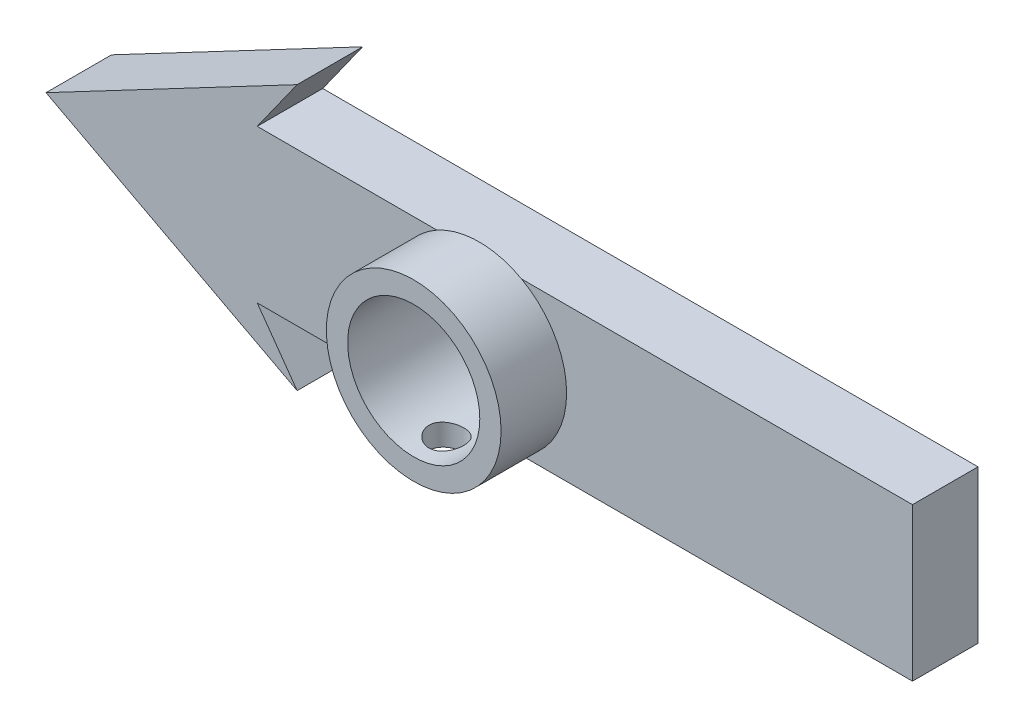
SolidWorks part; units mm, degrees
ref_plane "Front Plane" through (0, 0, 0) normal (0, 0, 1) x (1, 0, 0)
ref_plane "Top Plane" through (0, 0, 0) normal (0, 1, 0) x (1, 0, 0)
ref_plane "Right Plane" through (0, 0, 0) normal (1, 0, 0) x (0, 0, -1)
sketch "Sketch3" plane through (0, 0, 0) normal (0, 0, 1) x (1, 0, 0)
  line L0 (0, 0) -> (11.4976, 6.0667)
  line L1 (11.4976, 6.0667) -> (9.6701, 3.5)
  line L2 (9.6701, 3.5) -> (39.6701, 3.5)
  line L3 (39.6701, 3.5) -> (39.6701, -3.5)
  line L4 (3.3, 0) -> (-3.3, 0) construction
  line L5 (11.4976, -6.0667) -> (9.6701, -3.5)
  line L6 (9.6701, -3.5) -> (39.6701, -3.5)
  line L7 (0, 0) -> (11.4976, -6.0667)
  point P11 (39.6701, 0)
  dimension "D1" = 30
  dimension "D2" = 13
  dimension "D4" = 7
extrude "Boss-Extrude1" add sketch "Sketch3" along normal blind 3
sketch "Sketch8" plane through (0, 0, 3) normal (0, 0, 1) x (1, 0, 0)
  line L0 (0, 0) -> (39.6701, 0) construction
  line L1 (39.6701, -3.5) -> (39.6701, 3.5) construction
  circle A0 centre (19.835, 0) radius 4
  dimension "D1" = 8
extrude "Boss-Extrude4" add sketch "Sketch8" along normal blind 3
sketch "Sketch9" plane through (0, 0, 6) normal (0, 0, 1) x (1, 0, 0)
  circle A0 centre (19.835, 0) radius 3.025
  dimension "D1" = 6.05
extrude "Cut-Extrude5" cut sketch "Sketch9" against normal up to next
sketch "Sketch10" plane through (0, 0, 0) normal (0, 1, 0) x (1, 0, 0)
  line L0 (19.835, -3) -> (19.835, -6) construction
  line L1 (0, -3) -> (39.6701, -3) construction
  line L2 (16.81, -6) -> (22.86, -6) construction
  circle A0 centre (19.835, -4.5) radius 0.8
  dimension "D1" = 1.6
extrude "Cut-Extrude6" cut sketch "Sketch10" against normal up to next
